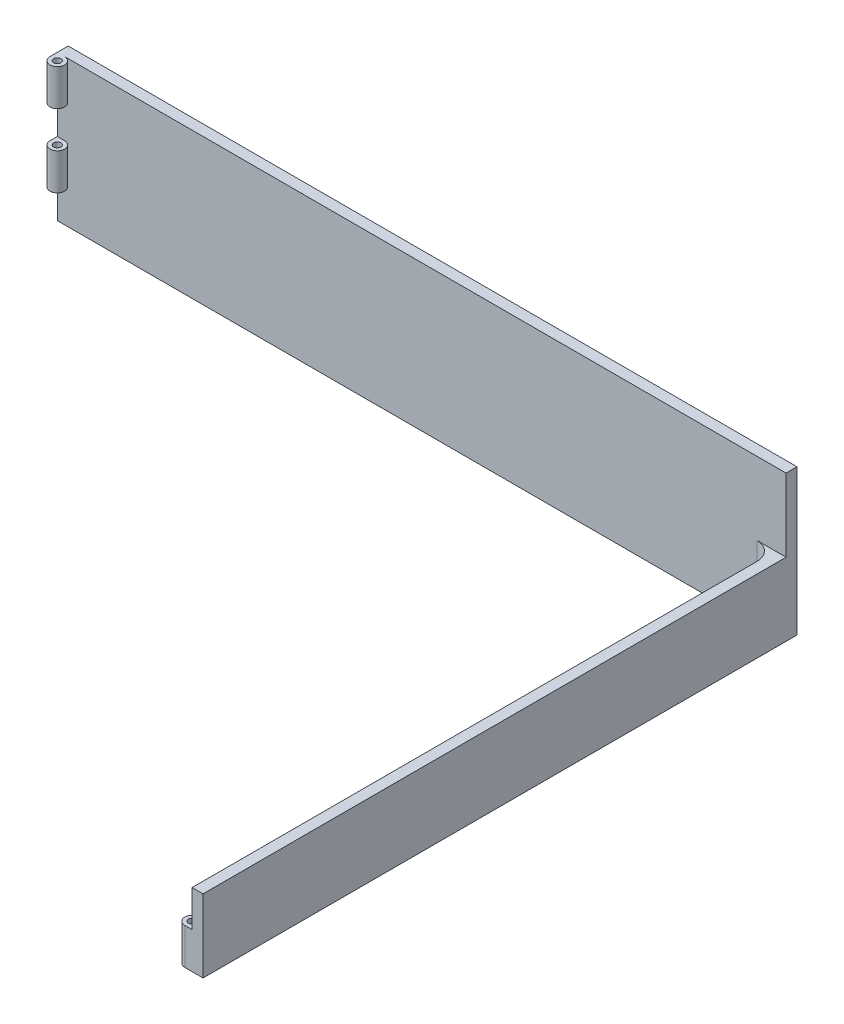
SolidWorks part; units mm, degrees
ref_plane "Front Plane" through (0, 0, 0) normal (0, 0, 1) x (1, 0, 0)
ref_plane "Top Plane" through (0, 0, 0) normal (0, 1, 0) x (1, 0, 0)
ref_plane "Right Plane" through (0, 0, 0) normal (1, 0, 0) x (0, 0, -1)
sketch "Sketch1" plane through (0, 0, 0) normal (0, 0, 1) x (1, 0, 0)
  line L1 (-153.405, 6.4875) -> (46.595, 6.4875)
  line L2 (-153.405, 6.4875) -> (-153.405, -33.5125)
  line L3 (-153.405, -33.5125) -> (46.595, -33.5125)
  line L4 (46.595, 6.4875) -> (46.595, -33.5125)
  line L5 (-153.405, 6.4875) -> (46.595, -33.5125) construction
  line L6 (-153.405, -33.5125) -> (46.595, 6.4875) construction
  point P0 (-53.405, -13.5125)
  dimension "D1" = 200
  dimension "D2" = 40
extrude "Boss-Extrude1" add sketch "Sketch1" along normal blind 3
sketch "Sketch2" plane through (46.595, 0, 0) normal (1, 0, 0) x (0, 0, -1)
  line L0 (-3, -13.5125) -> (-163, -13.5125)
  line L1 (-3, -33.5125) -> (-3, 6.4875) construction
  line L2 (-163, -13.5125) -> (-163, -33.5125)
  line L3 (-163, -33.5125) -> (-3, -33.5125)
  line L8 (0, -33.5125) -> (0, 6.4875)
  line L9 (0, 6.4875) -> (-3, 6.4875)
  line L10 (-3, 6.4875) -> (-3, -33.5125)
  line L11 (-3, -33.5125) -> (0, -33.5125)
  line L14 (-3, -13.5125) -> (-3, -33.5125)
  dimension "D2" = 160
  dimension "D1" = 0
extrude "Boss-Extrude2" add sketch "Sketch2" against normal blind 3
fillet "Fillet1" radius 5 1 edges at (43.595, -23.5125, 3)
sketch "Sketch3" plane through (0, 6.4875, 0) normal (0, 1, 0) x (1, 0, 0)
  line L0 (-153.405, -3) -> (-153.405, -5)
  line L1 (-153.405, -3) -> (-151.405, -3)
  line L2 (46.595, -3) -> (-153.405, -3) construction
  arc A0 (-153.405, -5) -> (-151.405, -3) centre (-151.405, -5) ccw
  circle A1 centre (-151.405, -5) radius 1
  dimension "D2" = 2
  dimension "D1" = 2
extrude "Boss-Extrude3" add sketch "Sketch3" against normal blind 10
pattern_linear "LPattern1" count 2 spacing 20 along (0, -1, 0) of "Boss-Extrude3"
sketch "Sketch4" plane through (0, -33.5125, 0) normal (0, -1, 0) x (1, 0, 0)
  line L0 (43.595, 163) -> (41.595, 163)
  line L1 (43.595, 163) -> (43.595, 161)
  line L2 (43.595, 163) -> (43.595, 8) construction
  arc A0 (43.595, 161) -> (41.595, 163) centre (41.595, 161) cw
  circle A1 centre (41.595, 161) radius 1
  dimension "D2" = 2
  dimension "D1" = 2
extrude "Boss-Extrude4" add sketch "Sketch4" against normal blind 10
